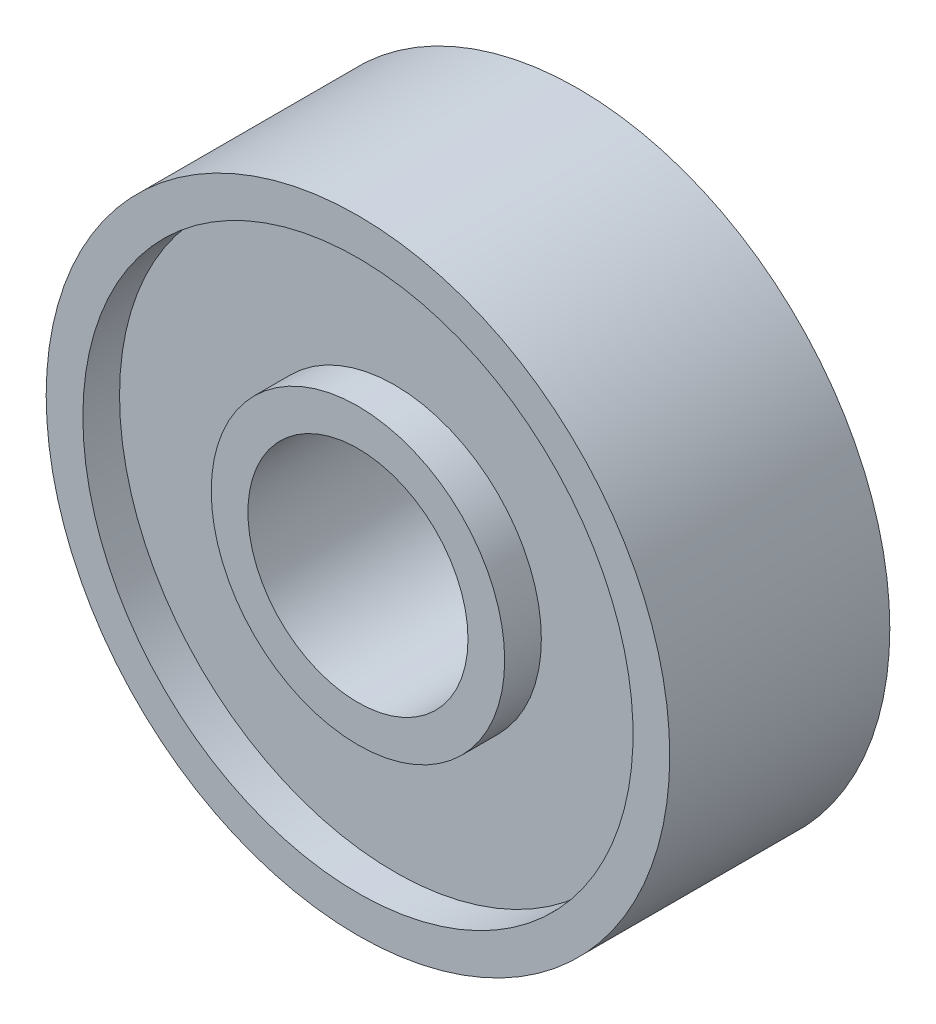
SolidWorks part; units mm, degrees
ref_plane "Front Plane" through (0, 0, 0) normal (0, 0, 1) x (1, 0, 0)
ref_plane "Top Plane" through (0, 0, 0) normal (0, 1, 0) x (1, 0, 0)
ref_plane "Right Plane" through (0, 0, 0) normal (1, 0, 0) x (0, 0, -1)
sketch "Sketch1" plane through (0, 0, 0) normal (0, 0, 1) x (1, 0, 0)
  circle A0 centre (0, 0) radius 8.5
  circle A1 centre (0, 0) radius 3
  dimension "D1" = 17
  dimension "D2" = 6
extrude "Boss-Extrude1" add sketch "Sketch1" along normal blind 6
sketch "Sketch2" plane through (0, 0, 0) normal (0, 1, 0) x (1, 0, 0)
  line L0 (0, 0) -> (0, -7.5431) construction
  line L3 (8.5, -6) -> (8.5, 0) construction
  line L4 (8.5, 0) -> (-8.5, 0) construction
  line L5 (4, 0) -> (7.5, 0)
  line L6 (4, 0) -> (4, -1)
  line L7 (4, -1) -> (7.5, -1)
  line L8 (7.5, 0) -> (7.5, -1)
  dimension "D1" = 1
  dimension "D3" = 1
revolve "Cut-Revolve1" cut sketch "Sketch2" angle 360 about L0
sketch "Sketch3" plane through (0, 0, 0) normal (0, 1, 0) x (1, 0, 0)
  line L0 (0, 0) -> (0, -6) construction
  line L1 (-8.5, -6) -> (8.5, -6) construction
  line L2 (4, -6) -> (7.5, -6)
  line L3 (4, -6) -> (4, -5)
  line L4 (4, -5) -> (7.5, -5)
  line L5 (7.5, -6) -> (7.5, -5)
  line L6 (8.5, -6) -> (8.5, 0) construction
  dimension "D1" = 6
  dimension "D2" = 4
  dimension "D3" = 1
  dimension "D4" = 1
revolve "Cut-Revolve2" cut sketch "Sketch3" angle 360 about L0
